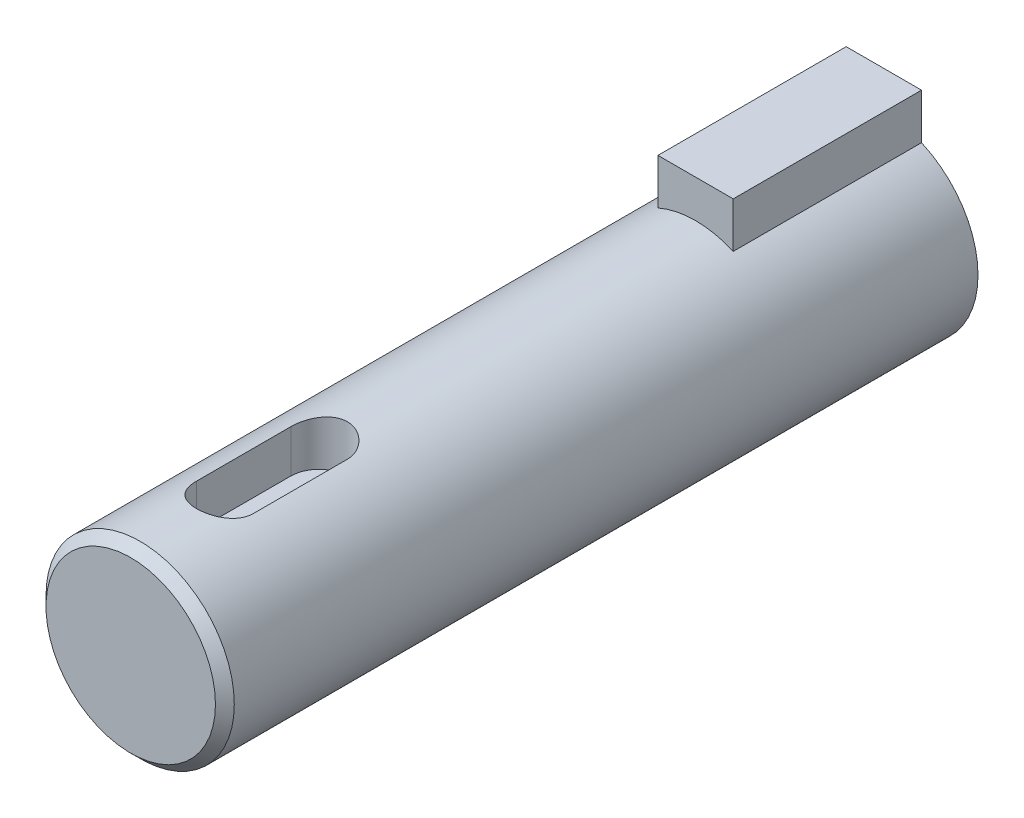
SolidWorks part; units mm, degrees
ref_plane "Front" through (0, 0, 0) normal (0, 0, 1) x (1, 0, 0)
ref_plane "Top" through (0, 0, 0) normal (0, 1, 0) x (1, 0, 0)
ref_plane "Right" through (0, 0, 0) normal (1, 0, 0) x (0, 0, -1)
sketch "Sketch1" plane through (0, 0, 0) normal (0, 0, 1) x (1, 0, 0)
  line L0 (0, 0) -> (0, 8.1299) construction
  line L2 (-2, 7) -> (2, 7)
  line L3 (-2, 7) -> (-2, 4.5826)
  line L5 (2, 7) -> (2, 4.5826)
  arc A0 (-2, 4.5826) -> (2, 4.5826) centre (0, 0) ccw
  point P8 (0, 0)
  dimension "D1" = 10
  dimension "D2" = 4
  dimension "D3" = 7
extrude "Boss-Extrude1" add sketch "Sketch1" along normal blind 10
sketch "Sketch2" plane through (0, 0, 10) normal (0, 0, 1) x (1, 0, 0)
  circle A0 centre (0, 0) radius 5
extrude "Boss-Extrude2" add sketch "Sketch2" along normal blind 30
sketch "Sketch3" plane through (0, 0, 0) normal (0, 1, 0) x (1, 0, 0)
  line L0 (0, -40) -> (0, 4.9471) construction
  line L1 (-5, -40) -> (5, -40) construction
  line L2 (0, -30) -> (0, -35) construction
  line L3 (1.5, -30) -> (1.5, -35)
  line L4 (-1.5, -30) -> (-1.5, -35)
  arc A0 (1.5, -30) -> (-1.5, -30) centre (0, -30) ccw
  arc A1 (-1.5, -35) -> (1.5, -35) centre (0, -35) ccw
  point P7 (0, -32.5)
  point P12 (1.5, -32.5)
  dimension "D1" = 3
  dimension "D2" = 5
  dimension "D3" = 5
extrude "Cut-Extrude2" cut sketch "Sketch3" along normal through all from offset 2.5
chamfer "Chamfer2" distance 0.5 angle 45 1 edges at (5, 0, 40)
